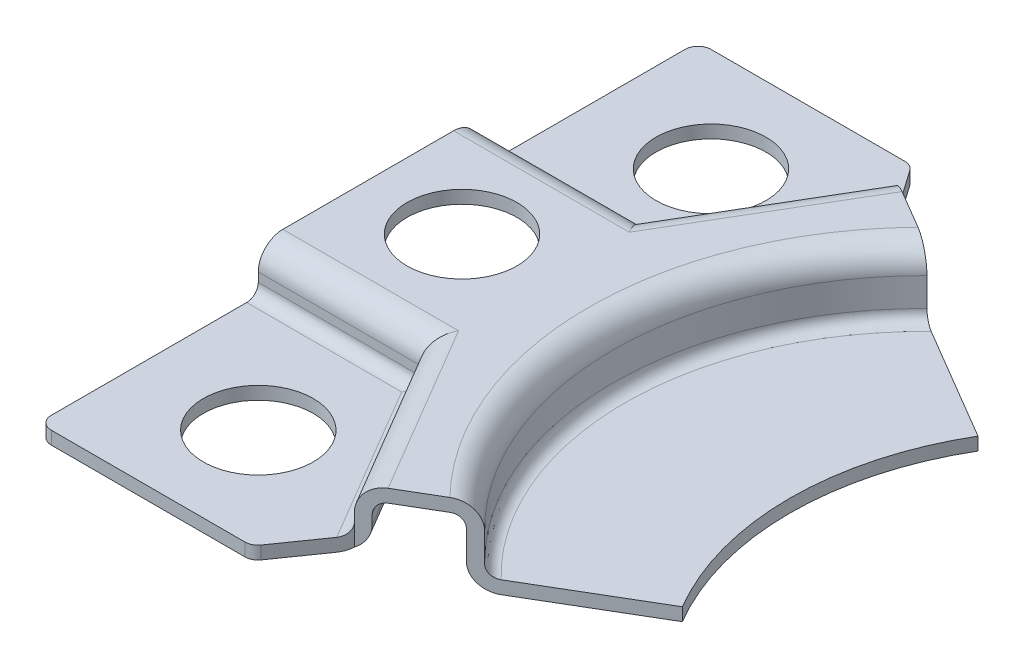
SolidWorks part; units mm, degrees
ref_plane "Спереди" through (0, 0, 0) normal (0, 0, 1) x (1, 0, 0)
ref_plane "Сверху" through (0, 0, 0) normal (0, 1, 0) x (1, 0, 0)
ref_plane "Справа" through (0, 0, 0) normal (1, 0, 0) x (0, 0, -1)
sketch "Эскиз1" plane through (0, 0, 0) normal (0, 1, 0) x (1, 0, 0)
  line L0 (0, 0) -> (25, 0)
  line L1 (0, 0) -> (0, 34)
  line L2 (0, 34) -> (33, 34)
  line L4 (39.5398, 24.6602) -> (25, 0)
  line L7 (39.5398, 24.6602) -> (33, 34)
  line L8 (39.5398, -58.6602) -> (33, -68)
  line L9 (-18.1957, -17) -> (94.9767, -17) construction
  line L10 (39.5398, -58.6602) -> (25, -34)
  line L11 (0, -68) -> (33, -68)
  line L12 (0, -34) -> (0, -68)
  line L13 (0, -34) -> (25, -34)
  circle A0 centre (18, 18) radius 8.5
  circle A1 centre (18, -52) radius 8.5
  dimension "D4" = 17
  dimension "D1" = 25
  dimension "D2" = 34
  dimension "D3" = 33
  dimension "D5" = 18
  dimension "D6" = 16
  dimension "D7" = 125
extrude "Бобышка-Вытянуть1" add sketch "Эскиз1" along normal blind 2
sketch "Эскиз2" plane through (0, 2, 0) normal (0, 1, 0) x (1, 0, 0)
  line L21 (0, 0) -> (0, -2)
  line L33 (0, 0) -> (25, 0)
  line L34 (0, -34) -> (25, -34)
  line L37 (39.5398, 24.6602) -> (41.2626, 23.6444)
  line L38 (41.2626, 23.6444) -> (26.1425, -2)
  line L39 (0, -2) -> (26.1425, -2)
  line L40 (39.5398, -58.6602) -> (41.2626, -57.6444)
  line L41 (41.2626, -57.6444) -> (26.1425, -32)
  line L42 (0, -34) -> (0, -32)
  line L43 (0, -32) -> (26.1425, -32)
  line L44 (25, 0) -> (39.5398, 24.6602)
  line L45 (25, -34) -> (39.5398, -58.6602)
extrude "Бобышка-Вытянуть7" add sketch "Эскиз2" along normal blind 5 and the other way blind 2
sketch "Эскиз4" plane through (0, 7, 0) normal (0, 1, 0) x (1, 0, 0)
  line L0 (0, -34) -> (25, -34)
  line L1 (25, -34) -> (39.5398, -58.6602)
  line L2 (-7.0755, -17) -> (66.8352, -17) construction
  line L3 (39.5398, -58.6602) -> (52.1988, -51.1964)
  line L4 (0, -34) -> (0, 0)
  line L5 (39.5398, 24.6602) -> (52.1988, 17.1964)
  line L6 (25, 0) -> (39.5398, 24.6602)
  line L7 (0, 0) -> (25, 0)
  arc A1 (52.1988, 17.1964) -> (52.1988, -51.1964) centre (85.8827, -17) ccw
  point P6 (0, -17)
  point P12 (0, -17)
  dimension "D1" = 96
extrude "Бобышка-Вытянуть8" add sketch "Эскиз4" along normal blind 2
fillet "Скругление1" radius 3.8 8 edges at (33.7026, 0, -10.8222) (33.7026, 0, 44.8222) (32.2699, 9, 46.3301) (12.5, 9, 34) (32.2699, 9, -12.3301) (12.5, 9, 0) (13.0713, 0, 32) (13.0713, 0, 2)
fillet "Скругление2" radius 1.8 8 edges at (32.2699, 2, 46.3301) (12.5, 2, 34) (33.7026, 7, 44.8222) (13.0713, 7, 32) (13.0713, 7, 2) (12.5, 2, 0) (32.2699, 2, -12.3301) (33.7026, 7, -10.8222)
sketch "Эскиз5" plane through (0, 9, 0) normal (0, 1, 0) x (1, 0, 0)
  circle A0 centre (14.5, -17) radius 8.5
  dimension "D1" = 17
extrude "Вырез-Вытянуть1" cut sketch "Эскиз5" against normal blind 2
sketch "Эскиз6" plane through (0, 7, 0) normal (0, -1, 0) x (1, 0, 0)
  line L0 (52.1988, -17.1964) -> (42.8132, -22.7302) construction
  line L1 (42.8132, 56.7302) -> (52.1988, 51.1964) construction
  line L2 (52.1988, -17.1964) -> (50.4184, -18.2461)
  line L3 (50.4184, 52.2461) -> (52.1988, 51.1964)
  arc A0 (52.1988, 51.1964) -> (52.1988, -17.1964) centre (85.8827, 17) ccw construction
  arc A1 (52.1988, 51.1964) -> (52.1988, -17.1964) centre (85.8827, 17) ccw
  arc A2 (50.4184, 52.2461) -> (50.4184, -18.2461) centre (85.8827, 17) ccw
  arc A3 (50.7953, 52.6213) -> (50.7953, -18.6213) centre (85.8827, 17) ccw construction
  dimension "D1" = 2
extrude "Бобышка-Вытянуть9" add sketch "Эскиз6" along normal blind 8
sketch "Эскиз7" plane through (0, -1, 0) normal (0, -1, 0) x (1, 0, 0)
  line L0 (50.4184, 52.2461) -> (71.4339, 39.8553)
  line L1 (50.4184, -18.2461) -> (71.4339, -5.8553)
  arc A0 (50.4184, 52.2461) -> (50.4184, -18.2461) centre (85.8827, 17) ccw construction
  arc A1 (50.4184, 52.2461) -> (50.4184, -18.2461) centre (85.8827, 17) ccw
  arc A3 (71.4339, 39.8553) -> (71.4339, -5.8553) centre (110.1977, 17) ccw
extrude "Бобышка-Вытянуть10" add sketch "Эскиз7" along normal blind 2
fillet "Скругление3" radius 1.8 2 edges at (37.8827, -1, 17) (35.8827, 7, 17)
fillet "Скругление4" radius 3.8 2 edges at (35.8827, -3, 17) (37.8827, 9, 17)
sketch "Эскиз8" plane through (0, 9, 0) normal (0, 1, 0) x (1, 0, 0)
  line L0 (6, -17) -> (23, -17)
  circle A0 centre (14.5, -17) radius 8.5 construction
fillet "Скругление5" radius 2 4 edges at (33, 1, 68) (0, 1, 68) (33, 1, -34) (0, 1, -34)
